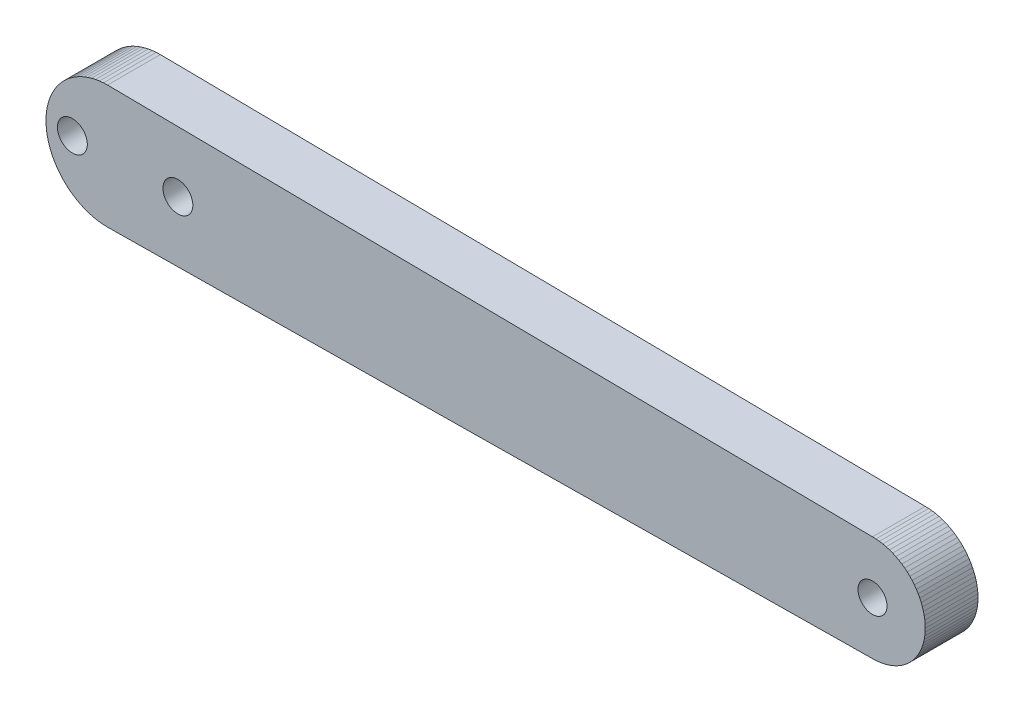
SolidWorks part; units mm, degrees
ref_plane "Front Plane" through (0, 0, 0) normal (0, 0, 1) x (1, 0, 0)
ref_plane "Top Plane" through (0, 0, 0) normal (0, 1, 0) x (1, 0, 0)
ref_plane "Right Plane" through (0, 0, 0) normal (1, 0, 0) x (0, 0, -1)
sketch "Sketch1" plane through (0, 0, 0) normal (0, 0, 1) x (1, 0, 0)
  line L0 (-2, 7) -> (-2.4578, 6.985)
  line L1 (-2.4578, 6.985) -> (-2.9137, 6.9401)
  line L2 (-2.9137, 6.9401) -> (-3.3656, 6.8655)
  line L3 (-3.3656, 6.8655) -> (-3.8117, 6.7615)
  line L4 (-3.8117, 6.7615) -> (-4.2501, 6.6285)
  line L5 (-4.2501, 6.6285) -> (-4.6788, 6.4672)
  line L6 (-4.6788, 6.4672) -> (-5.096, 6.2781)
  line L7 (-5.096, 6.2781) -> (-5.5, 6.0622)
  line L8 (-5.5, 6.0622) -> (-5.889, 5.8203)
  line L9 (-5.889, 5.8203) -> (-6.2613, 5.5535)
  line L10 (-6.2613, 5.5535) -> (-6.6154, 5.2629)
  line L11 (-6.6154, 5.2629) -> (-6.9497, 4.9497)
  line L12 (-6.9497, 4.9497) -> (-7.2629, 4.6154)
  line L13 (-7.2629, 4.6154) -> (-7.5535, 4.2613)
  line L14 (-7.5535, 4.2613) -> (-7.8203, 3.889)
  line L15 (-7.8203, 3.889) -> (-8.0622, 3.5)
  line L16 (-8.0622, 3.5) -> (-8.2781, 3.096)
  line L17 (-8.2781, 3.096) -> (-8.4672, 2.6788)
  line L18 (-8.4672, 2.6788) -> (-8.6285, 2.2501)
  line L19 (-8.6285, 2.2501) -> (-8.7615, 1.8117)
  line L20 (-8.7615, 1.8117) -> (-8.8655, 1.3656)
  line L21 (-8.8655, 1.3656) -> (-8.9401, 0.9137)
  line L22 (-8.9401, 0.9137) -> (-8.985, 0.4578)
  line L23 (-8.985, 0.4578) -> (-9, 0)
  line L24 (-9, 0) -> (-8.985, -0.4578)
  line L25 (-8.985, -0.4578) -> (-8.9401, -0.9137)
  line L26 (-8.9401, -0.9137) -> (-8.8655, -1.3656)
  line L27 (-8.8655, -1.3656) -> (-8.7615, -1.8117)
  line L28 (-8.7615, -1.8117) -> (-8.6285, -2.2501)
  line L29 (-8.6285, -2.2501) -> (-8.4672, -2.6788)
  line L30 (-8.4672, -2.6788) -> (-8.2781, -3.096)
  line L31 (-8.2781, -3.096) -> (-8.0622, -3.5)
  line L32 (-8.0622, -3.5) -> (-7.8203, -3.889)
  line L33 (-7.8203, -3.889) -> (-7.5535, -4.2613)
  line L34 (-7.5535, -4.2613) -> (-7.2629, -4.6154)
  line L35 (-7.2629, -4.6154) -> (-6.9497, -4.9497)
  line L36 (-6.9497, -4.9497) -> (-6.6154, -5.2629)
  line L37 (-6.6154, -5.2629) -> (-6.2613, -5.5535)
  line L38 (-6.2613, -5.5535) -> (-5.889, -5.8203)
  line L39 (-5.889, -5.8203) -> (-5.5, -6.0622)
  line L40 (-5.5, -6.0622) -> (-5.096, -6.2781)
  line L41 (-5.096, -6.2781) -> (-4.6788, -6.4672)
  line L42 (-4.6788, -6.4672) -> (-4.2501, -6.6285)
  line L43 (-4.2501, -6.6285) -> (-3.8117, -6.7615)
  line L44 (-3.8117, -6.7615) -> (-3.3656, -6.8655)
  line L45 (-3.3656, -6.8655) -> (-2.9137, -6.9401)
  line L46 (-2.9137, -6.9401) -> (-2.4578, -6.985)
  line L47 (-2.4578, -6.985) -> (-2, -7)
  line L48 (-2, -7) -> (85, -6)
  line L49 (85, -6) -> (85.3924, -5.9872)
  line L50 (85.3924, -5.9872) -> (85.7832, -5.9487)
  line L51 (85.7832, -5.9487) -> (86.1705, -5.8847)
  line L52 (86.1705, -5.8847) -> (86.5529, -5.7956)
  line L53 (86.5529, -5.7956) -> (86.9286, -5.6816)
  line L54 (86.9286, -5.6816) -> (87.2961, -5.5433)
  line L55 (87.2961, -5.5433) -> (87.6537, -5.3812)
  line L56 (87.6537, -5.3812) -> (88, -5.1962)
  line L57 (88, -5.1962) -> (88.3334, -4.9888)
  line L58 (88.3334, -4.9888) -> (88.6526, -4.7601)
  line L59 (88.6526, -4.7601) -> (88.9561, -4.511)
  line L60 (88.9561, -4.511) -> (89.2426, -4.2426)
  line L61 (89.2426, -4.2426) -> (89.511, -3.9561)
  line L62 (89.511, -3.9561) -> (89.7601, -3.6526)
  line L63 (89.7601, -3.6526) -> (89.9888, -3.3334)
  line L64 (89.9888, -3.3334) -> (90.1962, -3)
  line L65 (90.1962, -3) -> (90.3812, -2.6537)
  line L66 (90.3812, -2.6537) -> (90.5433, -2.2961)
  line L67 (90.5433, -2.2961) -> (90.6816, -1.9286)
  line L68 (90.6816, -1.9286) -> (90.7956, -1.5529)
  line L69 (90.7956, -1.5529) -> (90.8847, -1.1705)
  line L70 (90.8847, -1.1705) -> (90.9487, -0.7832)
  line L71 (90.9487, -0.7832) -> (90.9872, -0.3924)
  line L72 (90.9872, -0.3924) -> (91, 0)
  line L73 (91, 0) -> (90.9872, 0.3924)
  line L74 (90.9872, 0.3924) -> (90.9487, 0.7832)
  line L75 (90.9487, 0.7832) -> (90.8847, 1.1705)
  line L76 (90.8847, 1.1705) -> (90.7956, 1.5529)
  line L77 (90.7956, 1.5529) -> (90.6816, 1.9286)
  line L78 (90.6816, 1.9286) -> (90.5433, 2.2961)
  line L79 (90.5433, 2.2961) -> (90.3812, 2.6537)
  line L80 (90.3812, 2.6537) -> (90.1962, 3)
  line L81 (90.1962, 3) -> (89.9888, 3.3334)
  line L82 (89.9888, 3.3334) -> (89.7601, 3.6526)
  line L83 (89.7601, 3.6526) -> (89.511, 3.9561)
  line L84 (89.511, 3.9561) -> (89.2426, 4.2426)
  line L85 (89.2426, 4.2426) -> (88.9561, 4.511)
  line L86 (88.9561, 4.511) -> (88.6526, 4.7601)
  line L87 (88.6526, 4.7601) -> (88.3334, 4.9888)
  line L88 (88.3334, 4.9888) -> (88, 5.1962)
  line L89 (88, 5.1962) -> (87.6537, 5.3812)
  line L90 (87.6537, 5.3812) -> (87.2961, 5.5433)
  line L91 (87.2961, 5.5433) -> (86.9286, 5.6816)
  line L92 (86.9286, 5.6816) -> (86.5529, 5.7956)
  line L93 (86.5529, 5.7956) -> (86.1705, 5.8847)
  line L94 (86.1705, 5.8847) -> (85.7832, 5.9487)
  line L95 (85.7832, 5.9487) -> (85.3924, 5.9872)
  line L96 (85.3924, 5.9872) -> (85, 6)
  line L97 (85, 6) -> (-2, 7)
extrude "Plate" add sketch "Sketch1" along normal blind 6
sketch "Sketch2" plane through (0, 0, 0) normal (0, 0, 1) x (1, 0, 0)
  circle A0 centre (-6, 0) radius 1.7
  circle A1 centre (6, 0) radius 1.7
extrude "Hub_screws" cut sketch "Sketch2" along normal blind 6
sketch "Sketch3" plane through (0, 0, 0) normal (0, 0, 1) x (1, 0, 0)
  circle A0 centre (85, 0) radius 1.65
extrude "Knob_thread" cut sketch "Sketch3" along normal blind 6
